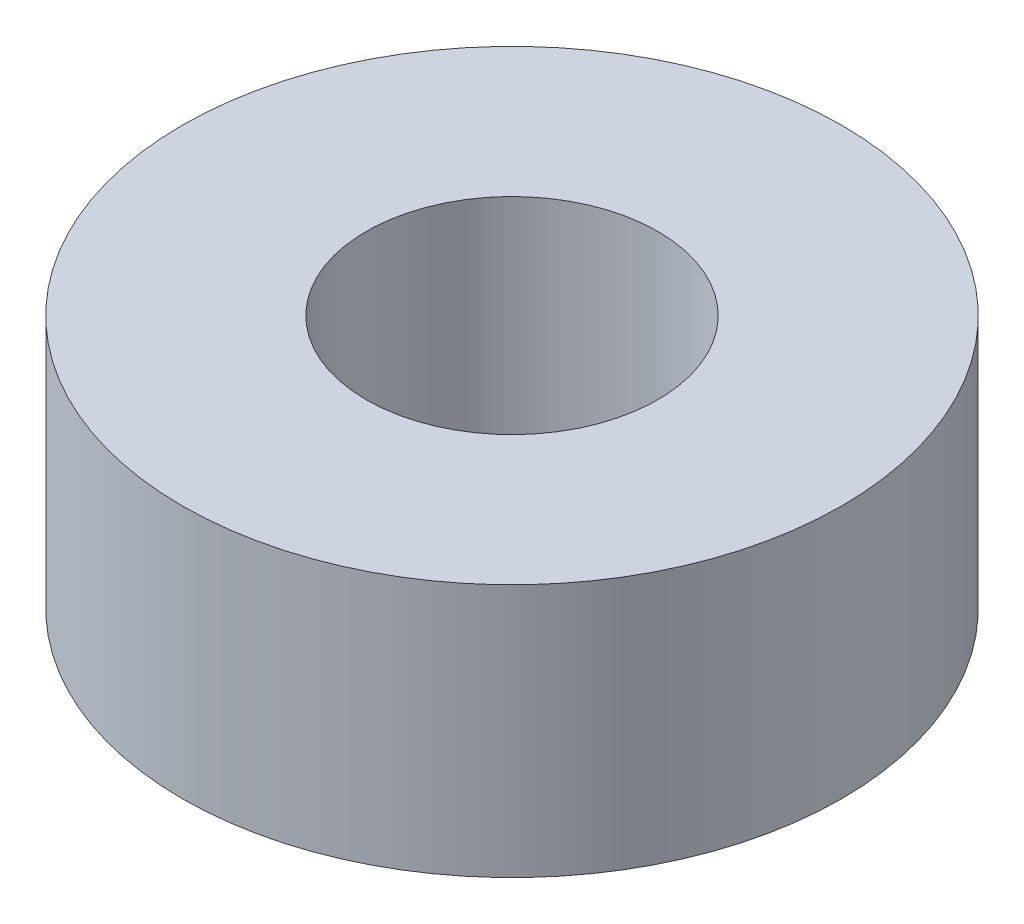
SolidWorks part; units mm, degrees
ref_plane "Front Plane" through (0, 0, 0) normal (0, 0, 1) x (1, 0, 0)
ref_plane "Top Plane" through (0, 0, 0) normal (0, 1, 0) x (1, 0, 0)
ref_plane "Right Plane" through (0, 0, 0) normal (1, 0, 0) x (0, 0, -1)
sketch "Sketch1" plane through (0, 0, 0) normal (0, 1, 0) x (1, 0, 0)
  circle A0 centre (0, 0) radius 26
  circle A1 centre (0, 0) radius 11.5
  dimension "D1" = 52
  dimension "D2" = 23
extrude "Boss-Extrude1" add sketch "Sketch1" along normal mid plane 20
